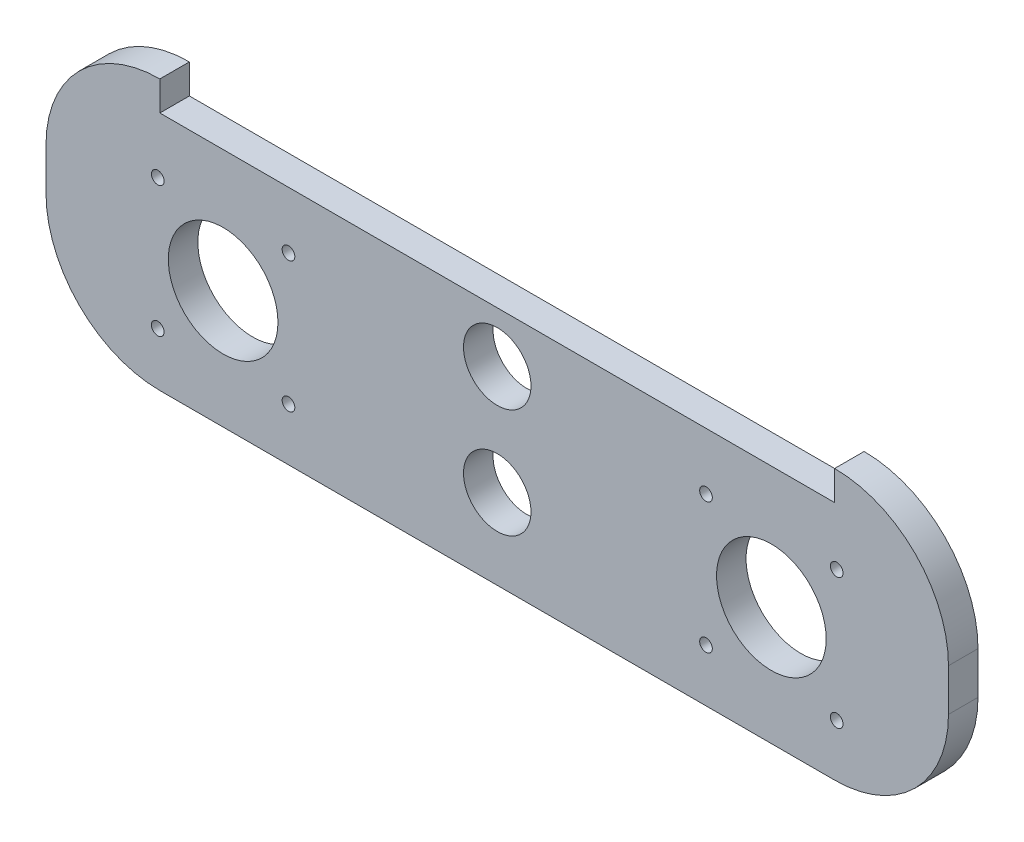
SolidWorks part; units mm, degrees
ref_plane "Piano frontale" through (0, 0, 0) normal (0, 0, 1) x (1, 0, 0)
ref_plane "Piano superiore" through (0, 0, 0) normal (0, 1, 0) x (1, 0, 0)
ref_plane "Piano destro" through (0, 0, 0) normal (1, 0, 0) x (0, 0, -1)
sketch "Schizzo1" plane through (0, 0, 0) normal (0, 0, 1) x (1, 0, 0)
  line L0 (-80, 32) -> (-80, 25)
  line L1 (-80, 25) -> (80, 25)
  line L2 (80, 25) -> (80, 32)
  line L3 (107, 5) -> (107, -5)
  line L4 (-107, 5) -> (-107, -5)
  line L5 (-80, -32) -> (80, -32)
  arc A0 (-80, 32) -> (-107, 5) centre (-80, 5) ccw
  arc A1 (-107, -5) -> (-80, -32) centre (-80, -5) ccw
  arc A2 (80, -32) -> (107, -5) centre (80, -5) ccw
  arc A3 (107, 5) -> (80, 32) centre (80, 5) ccw
  circle A4 centre (-65, -4.0002) radius 13
  circle A5 centre (-80.4998, 11.4996) radius 1.5
  circle A6 centre (-80.4998, -19.5) radius 1.5
  circle A7 centre (-49.5002, -19.5) radius 1.5
  circle A8 centre (-49.5002, 11.4996) radius 1.5
  circle A9 centre (65, -4.0002) radius 13
  circle A10 centre (49.5002, -19.5) radius 1.5
  circle A11 centre (80.4998, -19.5) radius 1.5
  circle A12 centre (80.4998, 11.4996) radius 1.5
  circle A13 centre (49.5002, 11.4996) radius 1.5
  circle A14 centre (0, 12.9413) radius 8
  circle A15 centre (0, -12.9413) radius 8
extrude "Estrusione-Estrusione1" add sketch "Schizzo1" along normal blind 7
